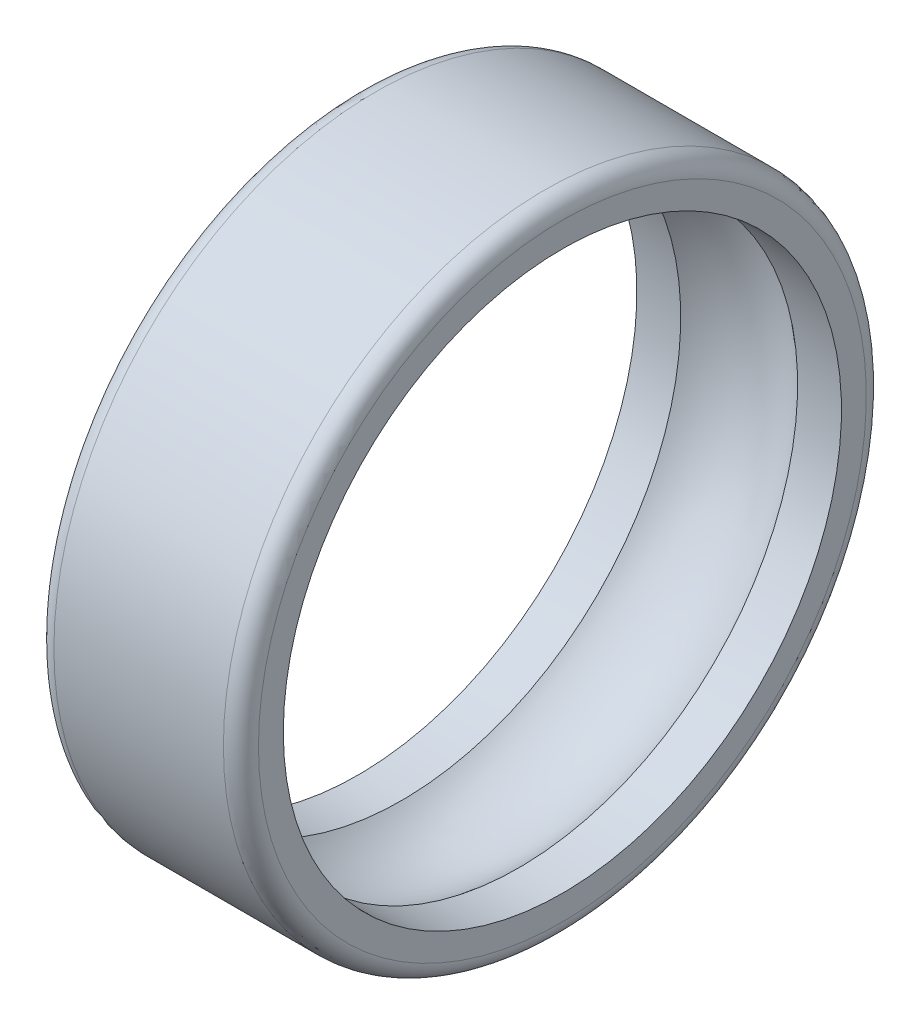
SolidWorks part; units mm, degrees
material "Nikel"
ref_plane "Ön Düzlem" through (0, 0, 0) normal (0, 0, 1) x (1, 0, 0)
ref_plane "Üst Düzlem" through (0, 0, 0) normal (0, 1, 0) x (1, 0, 0)
ref_plane "Sağ Düzlem" through (0, 0, 0) normal (1, 0, 0) x (0, 0, -1)
sketch "Çizim1" plane through (0, 0, 0) normal (0, 0, 1) x (1, 0, 0)
  line L0 (0, 10.2447) -> (0, 0) construction
  line L1 (-13.5511, 0) -> (18.5626, 0) construction
  line L2 (-3.5, 11) -> (3.5, 11)
  line L3 (-3.5, 11) -> (-3.5, 9.55)
  line L4 (-3.5, 9.55) -> (-2, 9.55)
  line L5 (3.5, 11) -> (3.5, 9.55)
  line L6 (-3.5, 11) -> (3.5, 9.55) construction
  line L7 (-3.5, 9.55) -> (3.5, 11) construction
  line L8 (2, 9.55) -> (3.5, 9.55)
  line L9 (0, 11) -> (0, 10.2447) construction
  arc A0 (-2, 9.55) -> (2, 9.55) centre (0, 7.3139) cw
  point P0 (0, 10.275)
  dimension "D1" = 7
  dimension "D2" = 11
  dimension "D3" = 9.55
revolve "Döndür1" add sketch "Çizim1" angle 360 about L1
fillet "Radyus1" radius 0.6 2 edges at (-3.5, 0, 11) (3.5, 0, 11)
